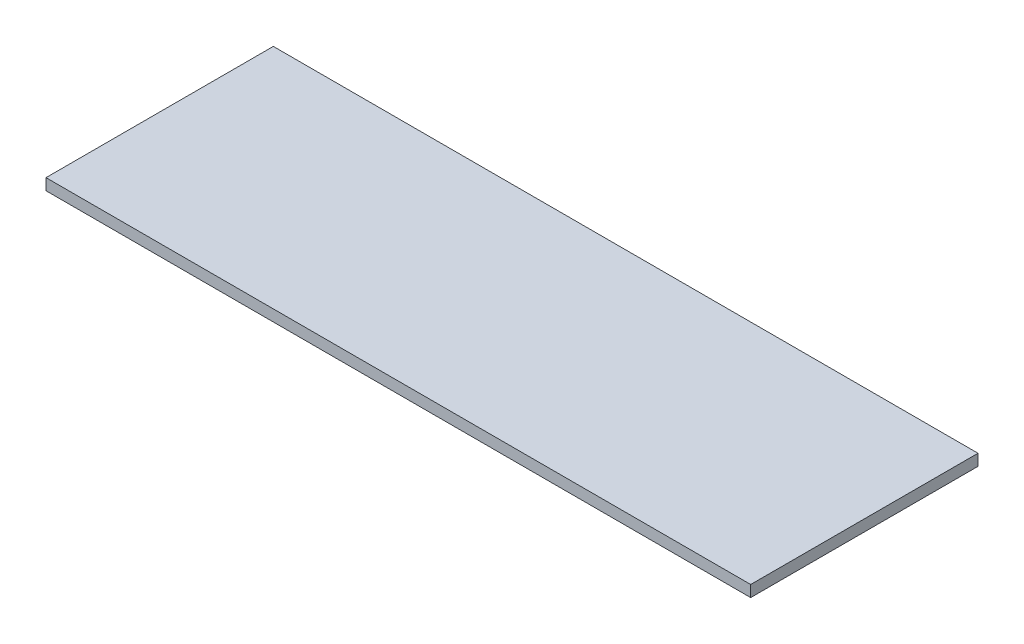
SolidWorks part; units mm, degrees
ref_plane "Front Plane" through (0, 0, 0) normal (0, 0, 1) x (1, 0, 0)
ref_plane "Top Plane" through (0, 0, 0) normal (0, 1, 0) x (1, 0, 0)
ref_plane "Right Plane" through (0, 0, 0) normal (1, 0, 0) x (0, 0, -1)
sketch "Sketch1" plane through (0, 0, 0) normal (0, 1, 0) x (1, 0, 0)
  line L1 (-98.425, 31.75) -> (98.425, 31.75)
  line L2 (-98.425, 31.75) -> (-98.425, -31.75)
  line L3 (-98.425, -31.75) -> (98.425, -31.75)
  line L4 (98.425, 31.75) -> (98.425, -31.75)
  line L5 (-98.425, 31.75) -> (98.425, -31.75) construction
  line L6 (-98.425, -31.75) -> (98.425, 31.75) construction
  point P0 (0, 0)
  dimension "D1" = 63.5
  dimension "D2" = 196.85
extrude "Boss-Extrude1" add sketch "Sketch1" along normal blind 3.175
